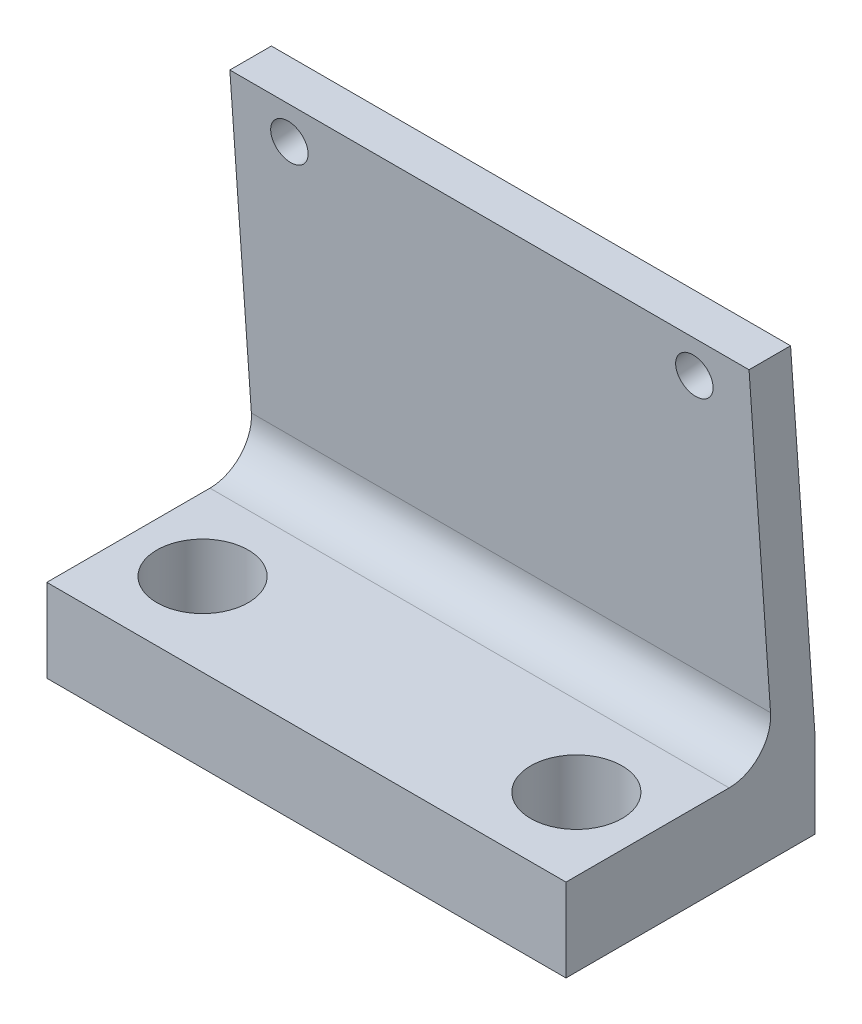
SolidWorks part; units mm, degrees
ref_plane "Plan de face" through (0, 0, 0) normal (0, 0, 1) x (1, 0, 0)
ref_plane "Plan de dessus" through (0, 0, 0) normal (0, 1, 0) x (1, 0, 0)
ref_plane "Plan de droite" through (0, 0, 0) normal (1, 0, 0) x (0, 0, -1)
sketch "Esquisse1" plane through (0, 0, 0) normal (0, 1, 0) x (1, 0, 0)
  line L0 (0, 27.0161) -> (0, -41.3306) construction
  line L1 (-12.5, 7.2581) -> (12.5, 7.2581)
  line L2 (-12.5, 7.2581) -> (-12.5, -4.7419)
  line L3 (-12.5, -4.7419) -> (12.5, -4.7419)
  line L4 (12.5, 7.2581) -> (12.5, -4.7419)
  line L5 (-17.4087, -0.7419) -> (17.2475, -0.7419) construction
  circle A0 centre (9, -0.7419) radius 2.2
  circle A1 centre (-9, -0.7419) radius 2.2
  dimension "D4" = 4.4
  dimension "D5" = 4.4
  dimension "D1" = 25
  dimension "D2" = 12
  dimension "D3" = 8
  dimension "D6" = 18
extrude "Boss.-Extru.1" add sketch "Esquisse1" along normal blind 4
sketch "Esquisse3" plane through (0, 4, 0) normal (0, 1, 0) x (1, 0, 0)
  line L0 (-12.5, 7.2581) -> (-12.5, -4.7419) construction
  line L1 (-12.5, 5.6641) -> (12.5, 5.6641)
  line L2 (-12.5, 5.6641) -> (-12.5, 2.8641)
  line L4 (12.5, 5.6641) -> (12.5, 2.8641)
  line L5 (12.5, -4.7419) -> (12.5, 7.2581) construction
  line L6 (0, 10.5345) -> (0, -11.0793) construction
  line L7 (-3.9603, 2.8641) -> (-12.5, 2.8641)
  line L8 (-3.9603, 2.8641) -> (-3.9603, -7.2687)
  line L9 (-3.9603, -7.2687) -> (3.9603, -7.2687)
  line L10 (3.9603, 2.8641) -> (3.9603, -7.2687)
  line L11 (3.9603, 2.8641) -> (12.5, 2.8641)
  dimension "D1" = 2.8
sketch "Esquisse4" plane through (-12.5, 0, 0) normal (-1, 0, 0) x (0, 0, 1)
  line L0 (-7.2581, 4) -> (-6.1615, 19.6816) construction
  line L1 (-7.2581, 4) -> (-7.2581, 0) construction
  dimension "D1" = 184
sketch "Esquisse5" plane through (0, 4, 0) normal (0, 1, 0) x (1, 0, 0)
  line L1 (-12.5, 7.2581) -> (12.5, 7.2581)
  line L2 (-12.5, 7.2581) -> (-12.5, 5.2581)
  line L3 (-12.5, 5.2581) -> (12.5, 5.2581)
  line L4 (12.5, 7.2581) -> (12.5, 5.2581)
  dimension "D1" = 2
extrude "Boss.-Extru.2" add sketch "Esquisse5" along direction (0, 0.9976, 0.0698) on the side of the normal blind 17
sketch "Esquisse6" plane through (0, 0.3854, -5.5108) normal (0, -0.0698, 0.9976) x (1, 0, 0)
  line L0 (0, 21.7414) -> (0, -2.4379) construction
  line L1 (12.5, 20.6235) -> (12.5, 3.6235) construction
  line L2 (-12.5, 3.484) -> (-12.5, 19.2039) construction
  circle A0 centre (-9.75, 18.9403) radius 0.9
  circle A1 centre (9.75, 18.9403) radius 0.9
  point P10 (0, 0)
  point P11 (-10.5281, 18.9403)
  dimension "D1" = 1.8
  dimension "D2" = 1.8
  dimension "D3" = 19.5
extrude "Enlèv. mat.-Extru.1" cut sketch "Esquisse6" against normal blind 17
fillet "Congé2" radius 2 1 edges at (0, 4, -5.2581)
